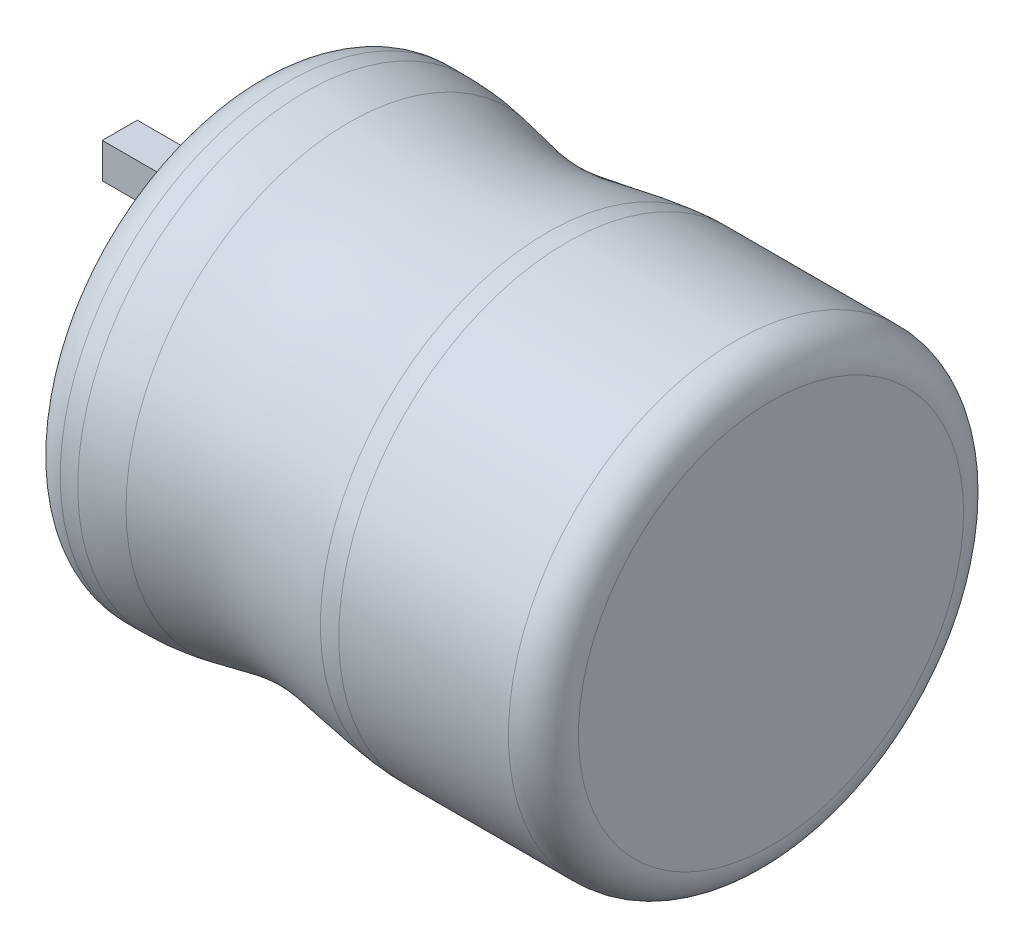
SolidWorks part; units mm, degrees
ref_plane "Přední rovina" through (0, 0, 0) normal (0, 0, 1) x (1, 0, 0)
ref_plane "Horní rovina" through (0, 0, 0) normal (0, 1, 0) x (1, 0, 0)
ref_plane "Pravá rovina" through (0, 0, 0) normal (1, 0, 0) x (0, 0, -1)
sketch "Skica1" plane through (0, 0, 0) normal (0, 0, 1) x (1, 0, 0)
  line L0 (0, 0) -> (0, 2.75)
  line L1 (0.5, 3.25) -> (0.7495, 3.25)
  line L2 (4.4779, 3.25) -> (6.9, 3.25)
  line L3 (7.4, 2.75) -> (7.4, 0)
  line L4 (7.4, 0) -> (0, 0)
  line L5 (-5.1544, 0) -> (14.9952, 0) construction
  arc A0 (4.2026, 3.2373) -> (4.4779, 3.25) centre (4.4779, 0.25) cw
  arc A1 (0.7495, 3.25) -> (1.3733, 3.1844) centre (0.7495, 0.25) cw
  arc A2 (0, 2.75) -> (0.5, 3.25) centre (0.5, 2.75) cw
  arc A3 (6.9, 3.25) -> (7.4, 2.75) centre (6.9, 2.75) cw
  spline S0 degree 3 poles (1.3733, 3.1844) (1.8441, 3.0843) (2.6375, 2.9131) (3.6799, 3.1892) (4.2026, 3.2373) knots 0.04974 0.04974 0.04974 0.04974 0.292962 0.585924 0.585924 0.585924 0.585924
  point P16 (0, 3.25)
  point P19 (7.4, 3.25)
  dimension "D3" = 3
  dimension "D4" = 0.5
  dimension "D1" = 6.5
  dimension "D2" = 6.5
  dimension "D5" = 7.4
revolve "Rotovat1" add sketch "Skica1" angle 360 about L4
sketch "Skica2" plane through (0, 0, 0) normal (-1, 0, 0) x (0, 0, 1)
  line L0 (1.9707, 0) -> (-1.7549, 0) construction
  line L1 (-0.25, -1.45) -> (0.25, -1.45)
  line L2 (-0.25, -1.45) -> (-0.25, -0.95)
  line L3 (-0.25, -0.95) -> (0.25, -0.95)
  line L4 (0.25, -1.45) -> (0.25, -0.95)
  line L6 (0.25, 0.95) -> (-0.25, 0.95)
  line L7 (0.25, 0.95) -> (0.25, 1.45)
  line L8 (0.25, 1.45) -> (-0.25, 1.45)
  line L9 (0, -2.4571) -> (0, 1.2) construction
  line L10 (-0.25, 0.95) -> (-0.25, 1.45)
  line L11 (0.25, 0.95) -> (-0.25, 1.45) construction
  line L12 (0.25, 1.45) -> (-0.25, 0.95) construction
  dimension "D1" = 0.5
  dimension "D2" = 0.5
  dimension "D3" = 0.5
  dimension "D4" = 0.5
  dimension "D5" = 1.9
extrude "Přidat vysunutím1" add sketch "Skica2" along normal blind 1.9
